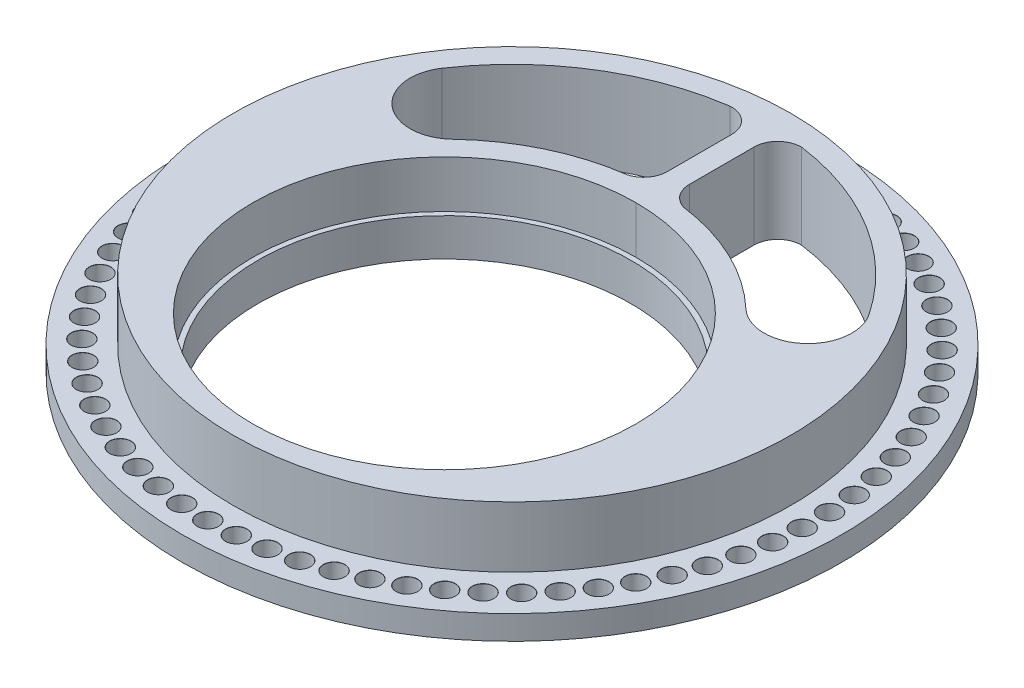
SolidWorks part; units mm, degrees
material "7075-T6, Plate (SS)"
ref_plane "X-Y Datum" through (0, 0, 0) normal (0, 0, 1) x (1, 0, 0)
ref_plane "X-Z Datum" through (0, 0, 0) normal (0, 1, 0) x (1, 0, 0)
ref_plane "Y-Z Datum" through (0, 0, 0) normal (1, 0, 0) x (0, 0, -1)
sketch "Sketch1" plane through (0, 0, 0) normal (0, 1, 0) x (1, 0, 0)
  line L0 (0, 0) -> (0, -12.7) construction
  line L1 (0, -43.0151) -> (0, 43.0151) construction
  line L2 (0, 61.9125) -> (0, 52.3875)
  circle A0 centre (0, -12.7) radius 35.052
  circle A1 centre (0, 0) radius 52.3875 construction
  circle A2 centre (0, 0) radius 57.15 construction
  circle A3 centre (0, 0) radius 61.9125
  point P12 (0, 57.15)
  dimension "D2" = 70.104
  dimension "D3" = 104.775
  dimension "D4" = 123.825
  dimension "D5" = 114.3
  dimension "D1" = 12.7
extrude "Boss-Extrude1" add sketch "Sketch1" along normal blind 4.5212
sketch "Sketch3" plane through (0, 4.5212, 0) normal (0, 1, 0) x (1, 0, 0)
  circle A0 centre (0, 0) radius 52.3875 construction
  circle A1 centre (0, 0) radius 52.3875
extrude "Boss-Extrude2" add sketch "Sketch3" along normal blind 11.43
sketch "Sketch4" plane through (0, 0, 0) normal (0, -1, 0) x (1, 0, 0)
  circle A0 centre (0, 12.7) radius 35.052 construction
  circle A1 centre (0, 12.7) radius 35.052
extrude "Cut-Extrude1" cut sketch "Sketch4" against normal through all
sketch "Sketch9" plane through (0, 15.9512, 0) normal (0, 1, 0) x (1, 0, 0)
  circle A0 centre (0, -12.7) radius 35.052 construction
  circle A1 centre (0, -12.7) radius 35.052 construction
  circle A2 centre (0, -12.7) radius 36
  dimension "D1" = 72
extrude "Cut-Extrude3" cut sketch "Sketch9" against normal blind 8.89
hole_wizard "Ø4.0mm Dowel Hole1" positions "Sketch7" profile "Sketch8" hole size "Ø4.0" standard "ANSI Metric" end condition through all
sketch "Sketch7" plane through (0, 4.5212, 0) normal (0, 1, 0) x (1, 0, 0)
  point P0 (0, 57.15)
sketch "Sketch8" plane through (0, 4.5212, -57.15) normal (1, 0, 0) x (0, 0, 1)
  line L0 (0, 0) -> (0, 4.5212)
  line L1 (0, 4.5212) -> (2, 4.5212)
  line L2 (2, 4.5212) -> (2, 0.025)
  line L3 (2, 0.025) -> (2.025, 0)
  line L5 (2.025, 0) -> (0, 0)
  line L6 (-2, 0.025) -> (-2.025, 0) construction
  line L11 (0, -6.35) -> (0, 107.95) construction
  dimension "Thru Hole Dia." = 4
  dimension "Thru Hole Depth" = 4.5212
  dimension "Near C'Sink Dia." = 4.05
  dimension "Near C'Sink Angle" = 90
pattern_circular "CirPattern1" count 70 over 360 about axis through (0, 0, 0) along (0, 1, 0) of "Ø4.0mm Dowel Hole1"
ref_point "Point1"
ref_plane "Plane1" through (0, 0, 0) normal (1, 0, 0) x (0, 0, -1)
split line "Split Line1"
ref_plane "Plane2" through (0, 7.9756, 0) normal (0, 1, 0) x (1, 0, 0)
sketch "Sketch14" plane through (0, 7.9756, 0) normal (0, 1, 0) x (1, 0, 0)
  circle A0 centre (-33.2491, 22.3603) radius 8.255
ref_point "Point4"
sketch "Sketch10" plane through (0, 15.9512, 0) normal (0, 1, 0) x (1, 0, 0)
  circle A0 centre (0, 0) radius 52.3875 construction
  circle A1 centre (0, 0) radius 52.3875 construction
  circle A3 centre (-33.2491, 22.3603) radius 8.255 construction
  circle A4 centre (33.2491, 22.3603) radius 8.255 construction
  arc A7 (0, -52.764) -> (0, 27.364) centre (0, -12.7) ccw
  arc A8 (0, 27.364) -> (0, -52.764) centre (0, -12.7) ccw
  arc A9 (0, -52.764) -> (0, 27.364) centre (0, -12.7) ccw construction
  arc A10 (0, 27.364) -> (0, -52.764) centre (0, -12.7) ccw construction
  circle A29 centre (0, 0) radius 48.3235 construction
  arc A30 (-27.5687, 16.3704) -> (27.5687, 16.3704) centre (0, -12.7) cw
  arc A31 (-40.0992, 26.967) -> (40.0992, 26.967) centre (0, 0) cw
  arc A32 (-40.0992, 26.967) -> (-27.5687, 16.3704) centre (-33.2491, 22.3603) ccw
  arc A33 (27.5687, 16.3704) -> (40.0992, 26.967) centre (33.2491, 22.3603) ccw
  dimension "D3" = 16.51
  dimension "D1" = 4.064
  dimension "D2" = 4.064
extrude "Cut-Extrude5" cut sketch "Sketch10" against normal through all contours A33 A31 A32 A30
sketch "Sketch15" plane through (0, 7.9756, 0) normal (0, 1, 0) x (1, 0, 0)
  line L1 (-2.1171, 31.2835) -> (-2.1171, 43.3958)
  line L4 (2.032, 31.291) -> (2.032, 43.4389)
  line L6 (-2.1764, 48.3235) -> (-2.1667, 48.2749) construction
  line L8 (2.1667, 48.2749) -> (2.1764, 48.3235) construction
  arc A0 (27.5687, 16.3704) -> (-27.5687, 16.3704) centre (0, -12.7) ccw construction
  arc A1 (27.5687, 16.3704) -> (-27.5687, 16.3704) centre (0, -12.7) ccw construction
  arc A2 (40.0992, 26.967) -> (-40.0992, 26.967) centre (0, 0) ccw construction
  arc A3 (-2.1171, 43.3958) -> (-6.9062, 47.8275) centre (-6.5621, 43.3958) ccw
  arc A4 (40.0992, 26.967) -> (-40.0992, 26.967) centre (0, 0) ccw construction
  arc A5 (6.5037, 47.8838) -> (2.032, 43.4389) centre (6.477, 43.4389) ccw
  arc A7 (-2.1171, 31.2835) -> (-5.362, 27.0036) centre (-6.5621, 31.2835) cw
  arc A9 (2.032, 31.291) -> (5.2509, 27.0184) centre (6.477, 31.291) ccw
  arc A10 (-6.9062, 47.8275) -> (6.5037, 47.8838) centre (0, 0) cw
  arc A11 (-5.362, 27.0036) -> (5.2509, 27.0184) centre (0, -12.7) cw
  point P4 (0, 0)
  point P9 (0, 37.4715)
  dimension "D1" = 4.445
  dimension "D2" = 2.1171
  dimension "D3" = 4.445
  dimension "D4" = 2.032
  dimension "D5" = 43.4389
  dimension "D6" = 31.2835
  dimension "D7" = 2.1171
  dimension "D8" = 12.148
  dimension "D9" = 12.1123
extrude "Boss-Extrude3" add sketch "Sketch15" along normal up to surface and the other way up to surface contours A9 L4 A5 A10 A3 L1 A7 A11 up to face at (0, 15.9512, -26.9504) other way up to face at (0, 0, -26.9504)
